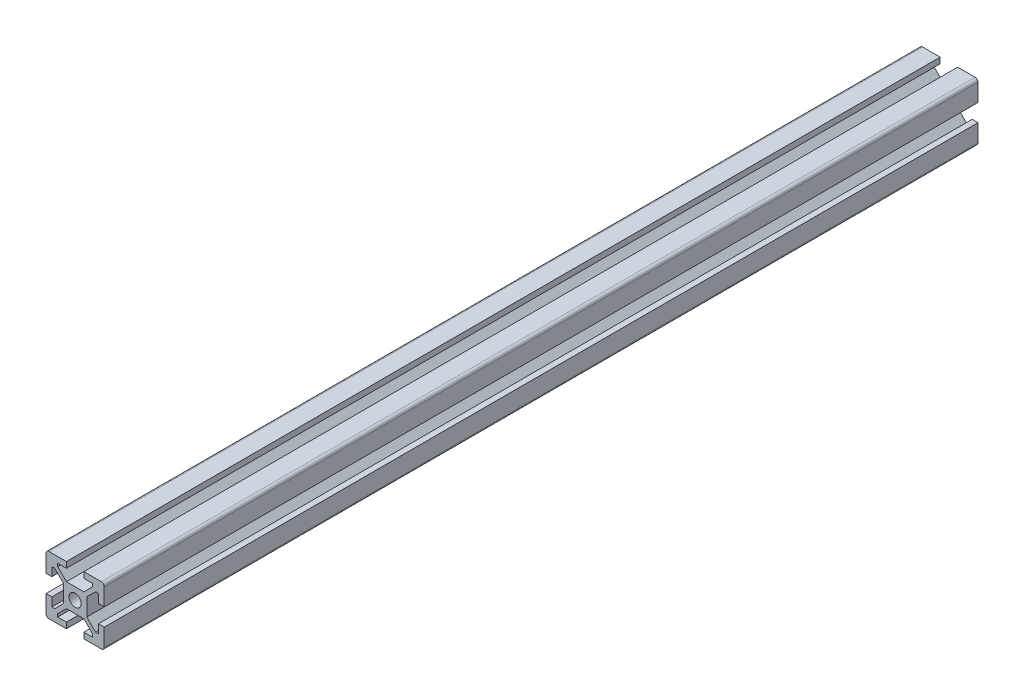
SolidWorks part; units mm, degrees
material "6063-O, Barra estrusa (SS)"
ref_plane "Piano frontale" through (0, 0, 0) normal (0, 0, 1) x (1, 0, 0)
ref_plane "Piano superiore" through (0, 0, 0) normal (0, 1, 0) x (1, 0, 0)
ref_plane "Piano destro" through (0, 0, 0) normal (1, 0, 0) x (0, 0, -1)
other "Lunghezza"
sketch "Schizzo1" plane through (0, 0, 0) normal (0, 0, 1) x (1, 0, 0)
  line L0 (-6, 8) -> (6, 8) construction
  line L1 (10, 3) -> (10, 10)
  line L2 (8, 3) -> (10, 3)
  line L3 (10, 10) -> (3, 10)
  line L4 (8, 6) -> (8, 3)
  line L5 (10, -10) -> (-10, 10) construction
  line L6 (10, 10) -> (-10, -10) construction
  line L7 (0, 23.5419) -> (0, -15.5419) construction
  line L8 (-13.4777, 0) -> (13.4408, 0) construction
  line L9 (-3, 4) -> (3, 4) construction
  line L10 (3, 4) -> (9, 10) construction
  line L11 (6, 11.4787) -> (6, 3.0667) construction
  line L12 (-6, 11.4787) -> (-6, 3.0667) construction
  line L13 (-3, 4) -> (-9, 10) construction
  line L14 (-3, 4) -> (-6, 7)
  line L15 (-6, 7) -> (-6, 8)
  line L16 (-6, 8) -> (-3, 8)
  line L17 (6, 8) -> (6, 7)
  line L18 (6, 7) -> (3, 4)
  line L19 (3, 4) -> (-3, 4)
  line L20 (-3, 8) -> (-3, 10)
  line L21 (6, 8) -> (3, 8)
  line L22 (3, 8) -> (3, 10)
  line L23 (-3, 10) -> (-10, 10)
  line L24 (7, 6) -> (8, 6)
  line L25 (4, 3) -> (7, 6)
  line L26 (4, -3) -> (4, 3)
  line L27 (7, -6) -> (4, -3)
  line L28 (8, -6) -> (7, -6)
  line L29 (8, -6) -> (8, -3)
  line L30 (8, -3) -> (10, -3)
  line L31 (10, -10) -> (10, -3)
  line L32 (3, -10) -> (10, -10)
  line L33 (3, -8) -> (3, -10)
  line L34 (6, -8) -> (3, -8)
  line L35 (6, -7) -> (6, -8)
  line L36 (3, -4) -> (6, -7)
  line L37 (-3, -4) -> (3, -4)
  line L38 (-6, -7) -> (-3, -4)
  line L39 (-6, -8) -> (-6, -7)
  line L40 (-6, -8) -> (-3, -8)
  line L41 (-3, -8) -> (-3, -10)
  line L42 (-10, -10) -> (-3, -10)
  line L43 (-10, -3) -> (-10, -10)
  line L44 (-8, -3) -> (-10, -3)
  line L45 (-8, -6) -> (-8, -3)
  line L46 (-7, -6) -> (-8, -6)
  line L47 (-4, -3) -> (-7, -6)
  line L48 (-4, 3) -> (-4, -3)
  line L49 (-7, 6) -> (-4, 3)
  line L50 (-8, 6) -> (-7, 6)
  line L51 (-8, 6) -> (-8, 3)
  line L52 (-8, 3) -> (-10, 3)
  line L53 (-10, 10) -> (-10, 3)
  circle A0 centre (0, 0) radius 2.1
  point P0 (0, 0)
  point P10 (0, 8)
  point P17 (0, 4)
  point P69 (0, 0)
  dimension "D6" = 4.2
  dimension "D1" = 20
  dimension "D2" = 10
  dimension "D3" = 2
  dimension "D4" = 12
  dimension "D5" = 4
  dimension "D7" = 4
  dimension "D8" = 6
  dimension "D9" = 6
  dimension "D10" = 3
  dimension "D11" = 4
extrude "Estrusione-Estrusione1" add sketch "Schizzo1" along normal blind 300
fillet "Raccordo1" radius 1 4 edges at (-10, -10, 150) (10, -10, 150) (-10, 10, 150) (10, 10, 150)
sketch "Sketch1" plane through (0, 0, 0) normal (1, 0, 0) x (0, 0, -1)
  line L0 (-150, 10) -> (-150, -10) construction
  line L1 (-300, 10) -> (0, 10) construction
  line L2 (0, -10) -> (-300, -10) construction
